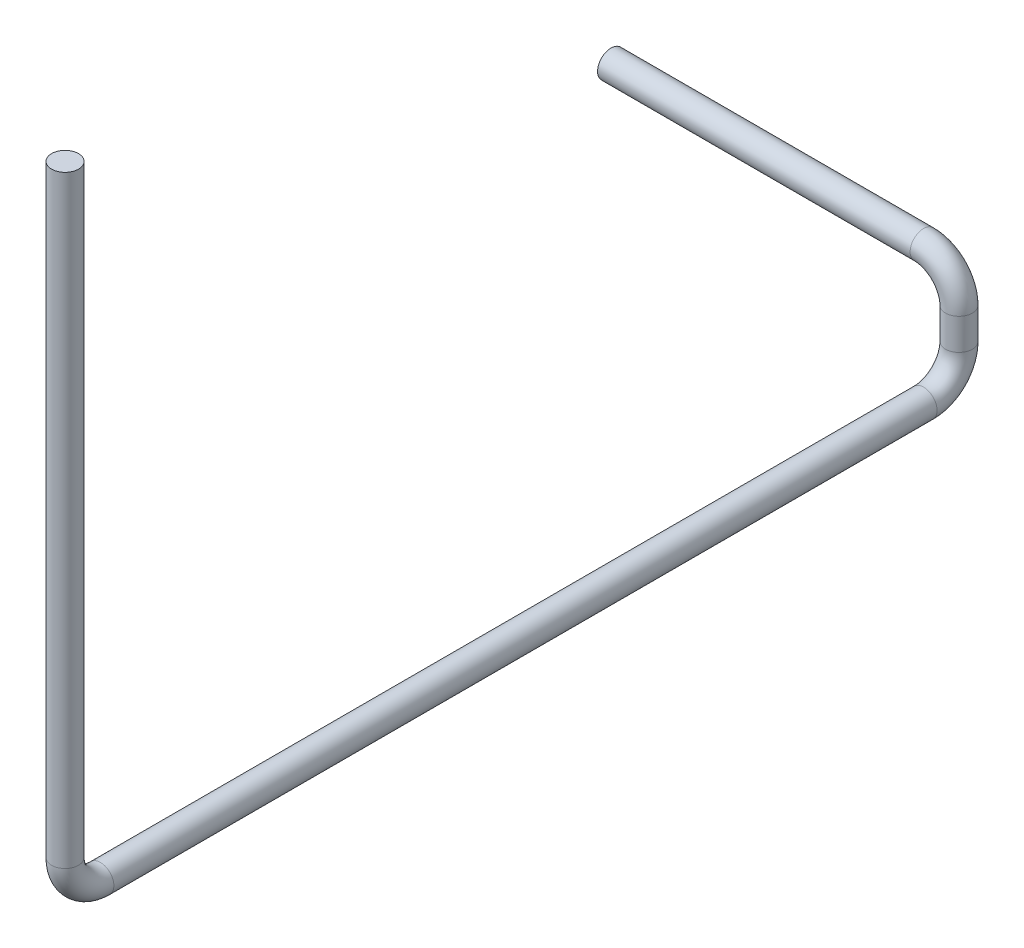
SolidWorks part; units mm, degrees
ref_plane "Alzado" through (0, 0, 0) normal (0, 0, 1) x (1, 0, 0)
ref_plane "Planta" through (0, 0, 0) normal (0, 1, 0) x (1, 0, 0)
ref_plane "Vista lateral" through (0, 0, 0) normal (1, 0, 0) x (0, 0, -1)
sketch3d "Croquis3D2"
  line L1 (1158.59, -243.39, 2257.05) -> (1600.4774, -243.39, 2257.05)
  line L2 (1650.4774, -293.39, 2257.05) -> (1650.4774, -337.5992, 2257.05)
  line L3 (1650.4774, -387.5992, 2307.05) -> (1650.4774, -387.5992, 3470.8059)
  line L4 (1650.4774, -337.5992, 3520.8059) -> (1650.4774, 514.7502, 3520.8059)
  arc A1 (1600.4774, -243.39, 2257.05) -> (1650.4774, -293.39, 2257.05) centre (1600.4774, -293.39, 2257.05) ccw
  arc A2 (1650.4774, -337.5992, 2257.05) -> (1650.4774, -387.5992, 2307.05) centre (1650.4774, -337.5992, 2307.05) ccw
  arc A3 (1650.4774, -387.5992, 3470.8059) -> (1650.4774, -337.5992, 3520.8059) centre (1650.4774, -337.5992, 3470.8059) ccw
  point P3 (1650.4774, -243.39, 2257.05)
  point P6 (1600.4774, -293.39, 2207.05)
  point P22 (1650.4774, -387.5992, 2257.05)
  point P23 (1600.4774, -337.5992, 2307.05)
  point P26 (1650.4774, -387.5992, 3520.8059)
  point P27 (1600.4774, -337.5992, 3470.8059)
  dimension "D1" = 50
  dimension "D2" = 491.8873
  dimension "D3" = 902.3494
  dimension "D4" = 1263.7559
  dimension "D5" = 144.2091
sweep "Barrer2" add path "Croquis3D2" circular profile diameter 38.1 parameters "D3"=38.1
